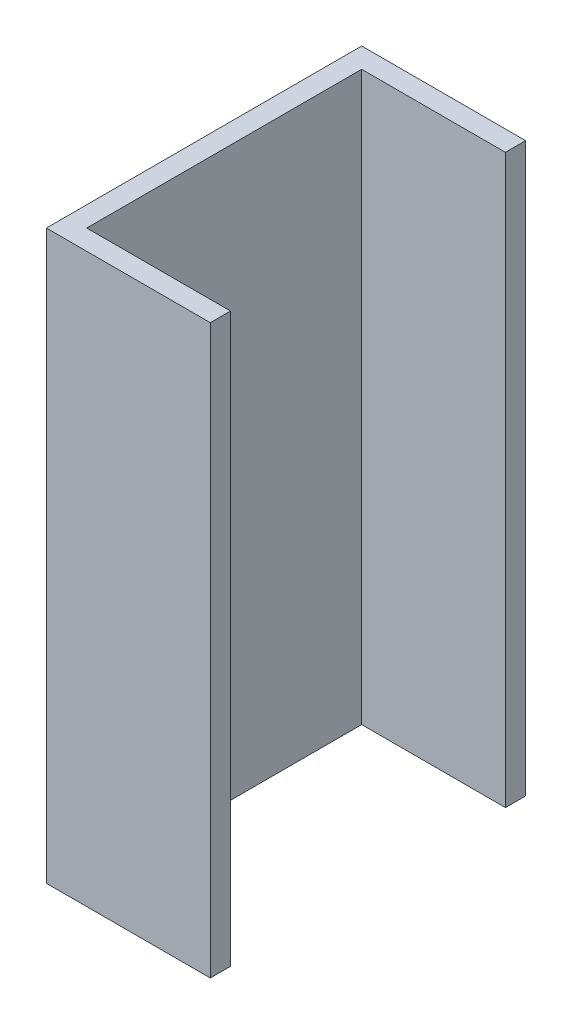
SolidWorks part; units mm, degrees
ref_plane "Front Plane" through (0, 0, 0) normal (0, 0, 1) x (1, 0, 0)
ref_plane "Top Plane" through (0, 0, 0) normal (0, 1, 0) x (1, 0, 0)
ref_plane "Right Plane" through (0, 0, 0) normal (1, 0, 0) x (0, 0, -1)
sketch "Sketch1" plane through (0, 0, 0) normal (0, 1, 0) x (1, 0, 0)
  line L0 (0, 0) -> (86.9787, 0) construction
  line L1 (0, -62.5) -> (0, 62.5)
  line L2 (0, 62.5) -> (65, 62.5)
  line L3 (65, 62.5) -> (65, 54.5)
  line L4 (65, 54.5) -> (8, 54.5)
  line L5 (8, 54.5) -> (8, -54.5)
  line L6 (65, -54.5) -> (8, -54.5)
  line L7 (65, -62.5) -> (65, -54.5)
  line L8 (0, -62.5) -> (65, -62.5)
  point P9 (8, 0)
  dimension "D1" = 125
  dimension "D2" = 65
  dimension "D3" = 8
  dimension "D4" = 8
extrude "Boss-Extrude1" add sketch "Sketch1" along normal mid plane 225
